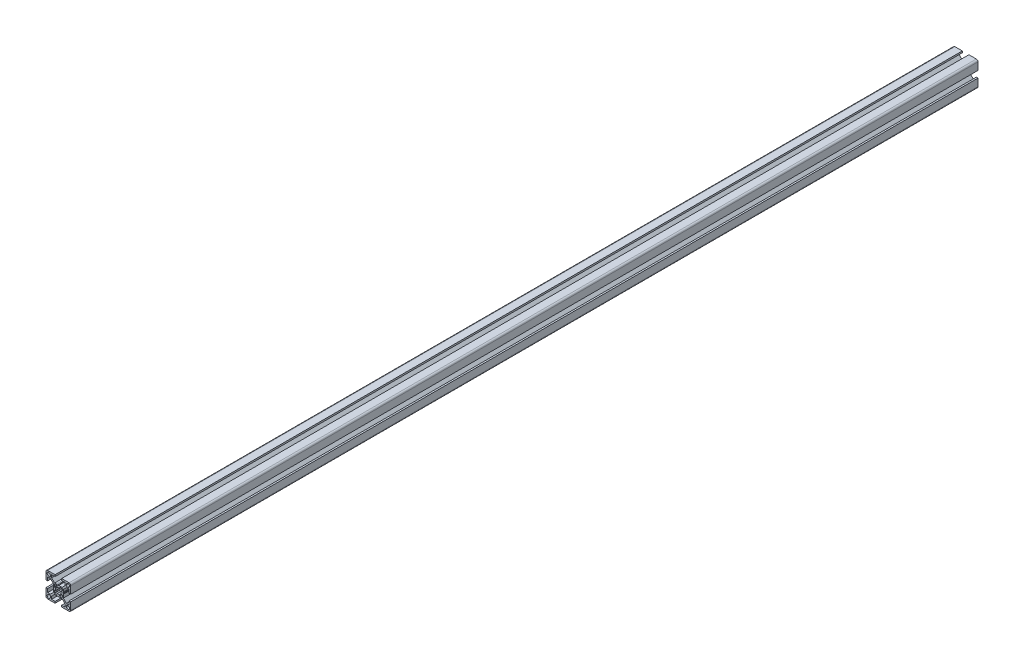
SolidWorks part; units mm, degrees
ref_plane "Front Plane" through (0, 0, 0) normal (0, 0, 1) x (1, 0, 0)
ref_plane "Top Plane" through (0, 0, 0) normal (0, 1, 0) x (1, 0, 0)
ref_plane "Right Plane" through (0, 0, 0) normal (1, 0, 0) x (0, 0, -1)
ref_plane "Plane1" through (0, 0, 0) normal (0, 0, 1) x (1, 0, 0)
sketch "Sketch1" plane through (0, 0, 0) normal (0, 0, 1) x (1, 0, 0)
  line L0 (-15, 4) -> (-13, 4)
  line L1 (-13, 4) -> (-13, 8.25)
  line L2 (-13, 8.25) -> (-9.6642, 8.25)
  line L3 (-9.6642, 8.25) -> (-6, 4.5858)
  line L4 (-6, 4.5858) -> (-6, 0.5196)
  line L5 (-6, 0.5196) -> (-5.7, 0)
  line L6 (-5.7, 0) -> (-5.933, -0.4036)
  line L7 (-5.933, -0.9036) -> (-5.751, -1.2189)
  line L8 (-5.751, -1.2189) -> (-6, -2.5)
  line L9 (-6, -2.5) -> (-6, -4.5858)
  line L10 (-6, -4.5858) -> (-9.6642, -8.25)
  line L11 (-9.6642, -8.25) -> (-13, -8.25)
  line L12 (-13, -8.25) -> (-13, -4)
  line L13 (-13, -4) -> (-15, -4)
  line L14 (-15, -4) -> (-15, -13)
  line L15 (-13, -15) -> (-4, -15)
  line L16 (-4, -15) -> (-4, -13)
  line L17 (-4, -13) -> (-8.25, -13)
  line L18 (-8.25, -13) -> (-8.25, -9.6642)
  line L19 (-8.25, -9.6642) -> (-4.5858, -6)
  line L20 (-4.5858, -6) -> (-0.5196, -6)
  line L21 (-0.5196, -6) -> (0, -5.7)
  line L22 (0, -5.7) -> (0.4036, -5.933)
  line L23 (0.9036, -5.933) -> (1.2189, -5.751)
  line L24 (1.2189, -5.751) -> (2.5, -6)
  line L25 (2.5, -6) -> (4.5858, -6)
  line L26 (4.5858, -6) -> (8.25, -9.6642)
  line L27 (8.25, -9.6642) -> (8.25, -13)
  line L28 (8.25, -13) -> (4, -13)
  line L29 (4, -13) -> (4, -15)
  line L30 (4, -15) -> (13, -15)
  line L31 (15, -13) -> (15, -4)
  line L32 (15, -4) -> (13, -4)
  line L33 (13, -4) -> (13, -8.25)
  line L34 (13, -8.25) -> (9.6642, -8.25)
  line L35 (9.6642, -8.25) -> (6, -4.5858)
  line L36 (6, -4.5858) -> (6, -0.5196)
  line L37 (6, -0.5196) -> (5.7, 0)
  line L38 (5.7, 0) -> (5.933, 0.4036)
  line L39 (5.933, 0.9036) -> (5.751, 1.2189)
  line L40 (5.751, 1.2189) -> (6, 2.5)
  line L41 (6, 2.5) -> (6, 4.5858)
  line L42 (6, 4.5858) -> (9.6642, 8.25)
  line L43 (9.6642, 8.25) -> (13, 8.25)
  line L44 (13, 8.25) -> (13, 4)
  line L45 (13, 4) -> (15, 4)
  line L46 (15, 4) -> (15, 13)
  line L47 (13, 15) -> (4, 15)
  line L48 (4, 15) -> (4, 13)
  line L49 (4, 13) -> (8.25, 13)
  line L50 (8.25, 13) -> (8.25, 9.6642)
  line L51 (8.25, 9.6642) -> (4.5858, 6)
  line L52 (4.5858, 6) -> (0.5196, 6)
  line L53 (0.5196, 6) -> (0, 5.7)
  line L54 (0, 5.7) -> (-0.4036, 5.933)
  line L55 (-0.9036, 5.933) -> (-1.2189, 5.751)
  line L56 (-1.2189, 5.751) -> (-2.5, 6)
  line L57 (-2.5, 6) -> (-4.5858, 6)
  line L58 (-4.5858, 6) -> (-8.25, 9.6642)
  line L59 (-8.25, 9.6642) -> (-8.25, 13)
  line L60 (-8.25, 13) -> (-4, 13)
  line L61 (-4, 13) -> (-4, 15)
  line L62 (-4, 15) -> (-13, 15)
  line L63 (-15, 13) -> (-15, 4)
  line L64 (11.3389, 9.5391) -> (12.3615, 9.9189)
  line L65 (9.9189, 12.3615) -> (9.5391, 11.3389)
  line L66 (9.5391, -11.3389) -> (9.9189, -12.3615)
  line L67 (12.3615, -9.9189) -> (11.3389, -9.5391)
  line L68 (-12.3615, 9.9189) -> (-11.3389, 9.5391)
  line L69 (-9.5391, 11.3389) -> (-9.9189, 12.3615)
  line L70 (-9.9189, -12.3615) -> (-9.5391, -11.3389)
  line L71 (-11.3389, -9.5391) -> (-12.3615, -9.9189)
  arc A0 (-5.933, -0.4036) -> (-5.933, -0.9036) centre (-5.5, -0.6536) ccw
  arc A1 (-15, -13) -> (-13, -15) centre (-13, -13) ccw
  arc A2 (0.4036, -5.933) -> (0.9036, -5.933) centre (0.6536, -5.5) ccw
  arc A3 (13, -15) -> (15, -13) centre (13, -13) ccw
  arc A4 (5.933, 0.4036) -> (5.933, 0.9036) centre (5.5, 0.6536) ccw
  arc A5 (15, 13) -> (13, 15) centre (13, 13) ccw
  arc A6 (-0.4036, 5.933) -> (-0.9036, 5.933) centre (-0.6536, 5.5) ccw
  arc A7 (-13, 15) -> (-15, 13) centre (-13, 13) ccw
  arc A8 (9.5391, 11.3389) -> (11.3389, 9.5391) centre (10.8515, 10.8515) ccw
  arc A9 (12.3615, 9.9189) -> (9.9189, 12.3615) centre (11.7, 11.7) ccw
  arc A10 (11.3389, -9.5391) -> (9.5391, -11.3389) centre (10.8515, -10.8515) ccw
  arc A11 (9.9189, -12.3615) -> (12.3615, -9.9189) centre (11.7, -11.7) ccw
  arc A12 (-9.9189, 12.3615) -> (-12.3615, 9.9189) centre (-11.7, 11.7) ccw
  arc A13 (-11.3389, 9.5391) -> (-9.5391, 11.3389) centre (-10.8515, 10.8515) ccw
  arc A14 (-12.3615, -9.9189) -> (-9.9189, -12.3615) centre (-11.7, -11.7) ccw
  arc A15 (-9.5391, -11.3389) -> (-11.3389, -9.5391) centre (-10.8515, -10.8515) ccw
extrude "Boss-Extrude1" add sketch "Sketch1" against normal blind 1100
ref_plane "Plane2" through (0, 0, 0) normal (0, 0, 1) x (1, 0, 0)
sketch "Sketch2" plane through (0, 0, 0) normal (0, 0, 1) x (1, 0, 0)
  line L0 (-4.5, -4.8) -> (-2.6444, -4.8)
  line L1 (-2.5872, -4.7945) -> (-1.7428, -4.6303)
  line L2 (-1.5, -4.3359) -> (-1.5, -3.5)
  line L3 (1.5, -3.5) -> (1.5, -4.3359)
  line L4 (1.7428, -4.6303) -> (2.5872, -4.7945)
  line L5 (2.6444, -4.8) -> (4.5, -4.8)
  line L6 (4.8, -4.5) -> (4.8, -2.6444)
  line L7 (4.7945, -2.5872) -> (4.6303, -1.7428)
  line L8 (4.3359, -1.5) -> (3.5, -1.5)
  line L9 (3.5, 1.5) -> (4.3359, 1.5)
  line L10 (4.6303, 1.7428) -> (4.7945, 2.5872)
  line L11 (4.8, 2.6444) -> (4.8, 4.5)
  line L12 (4.5, 4.8) -> (2.6444, 4.8)
  line L13 (2.5872, 4.7945) -> (1.7428, 4.6303)
  line L14 (1.5, 4.3359) -> (1.5, 3.5)
  line L15 (-1.5, 3.5) -> (-1.5, 4.3359)
  line L16 (-1.7428, 4.6303) -> (-2.5872, 4.7945)
  line L17 (-2.6444, 4.8) -> (-4.5, 4.8)
  line L18 (-4.8, 4.5) -> (-4.8, 2.6444)
  line L19 (-4.7945, 2.5872) -> (-4.6303, 1.7428)
  line L20 (-4.3359, 1.5) -> (-3.5, 1.5)
  line L21 (-3.5, -1.5) -> (-4.3359, -1.5)
  line L22 (-4.6303, -1.7428) -> (-4.7945, -2.5872)
  line L23 (-4.8, -2.6444) -> (-4.8, -4.5)
  arc A0 (-4.8, -4.5) -> (-4.5, -4.8) centre (-4.5, -4.5) ccw
  arc A1 (-2.6444, -4.8) -> (-2.5872, -4.7945) centre (-2.6444, -4.5) ccw
  arc A2 (-1.7428, -4.6303) -> (-1.5, -4.3359) centre (-1.8, -4.3359) ccw
  arc A3 (-1.5, -3.5) -> (-1.1027, -3.2162) centre (-1.2, -3.5) cw
  arc A4 (-1.1027, -3.2162) -> (1.1027, -3.2162) centre (0, 0) ccw
  arc A5 (1.1027, -3.2162) -> (1.5, -3.5) centre (1.2, -3.5) cw
  arc A6 (1.5, -4.3359) -> (1.7428, -4.6303) centre (1.8, -4.3359) ccw
  arc A7 (2.5872, -4.7945) -> (2.6444, -4.8) centre (2.6444, -4.5) ccw
  arc A8 (4.5, -4.8) -> (4.8, -4.5) centre (4.5, -4.5) ccw
  arc A9 (4.8, -2.6444) -> (4.7945, -2.5872) centre (4.5, -2.6444) ccw
  arc A10 (4.6303, -1.7428) -> (4.3359, -1.5) centre (4.3359, -1.8) ccw
  arc A11 (3.5, -1.5) -> (3.2162, -1.1027) centre (3.5, -1.2) cw
  arc A12 (3.2162, -1.1027) -> (3.2162, 1.1027) centre (0, 0) ccw
  arc A13 (3.2162, 1.1027) -> (3.5, 1.5) centre (3.5, 1.2) cw
  arc A14 (4.3359, 1.5) -> (4.6303, 1.7428) centre (4.3359, 1.8) ccw
  arc A15 (4.7945, 2.5872) -> (4.8, 2.6444) centre (4.5, 2.6444) ccw
  arc A16 (4.8, 4.5) -> (4.5, 4.8) centre (4.5, 4.5) ccw
  arc A17 (2.6444, 4.8) -> (2.5872, 4.7945) centre (2.6444, 4.5) ccw
  arc A18 (1.7428, 4.6303) -> (1.5, 4.3359) centre (1.8, 4.3359) ccw
  arc A19 (1.5, 3.5) -> (1.1027, 3.2162) centre (1.2, 3.5) cw
  arc A20 (1.1027, 3.2162) -> (-1.1027, 3.2162) centre (0, 0) ccw
  arc A21 (-1.1027, 3.2162) -> (-1.5, 3.5) centre (-1.2, 3.5) cw
  arc A22 (-1.5, 4.3359) -> (-1.7428, 4.6303) centre (-1.8, 4.3359) ccw
  arc A23 (-2.5872, 4.7945) -> (-2.6444, 4.8) centre (-2.6444, 4.5) ccw
  arc A24 (-4.5, 4.8) -> (-4.8, 4.5) centre (-4.5, 4.5) ccw
  arc A25 (-4.8, 2.6444) -> (-4.7945, 2.5872) centre (-4.5, 2.6444) ccw
  arc A26 (-4.6303, 1.7428) -> (-4.3359, 1.5) centre (-4.3359, 1.8) ccw
  arc A27 (-3.5, 1.5) -> (-3.2162, 1.1027) centre (-3.5, 1.2) cw
  arc A28 (-3.2162, 1.1027) -> (-3.2162, -1.1027) centre (0, 0) ccw
  arc A29 (-3.2162, -1.1027) -> (-3.5, -1.5) centre (-3.5, -1.2) cw
  arc A30 (-4.3359, -1.5) -> (-4.6303, -1.7428) centre (-4.3359, -1.8) ccw
  arc A31 (-4.7945, -2.5872) -> (-4.8, -2.6444) centre (-4.5, -2.6444) ccw
extrude "Cut-Extrude1" cut sketch "Sketch2" against normal through all
